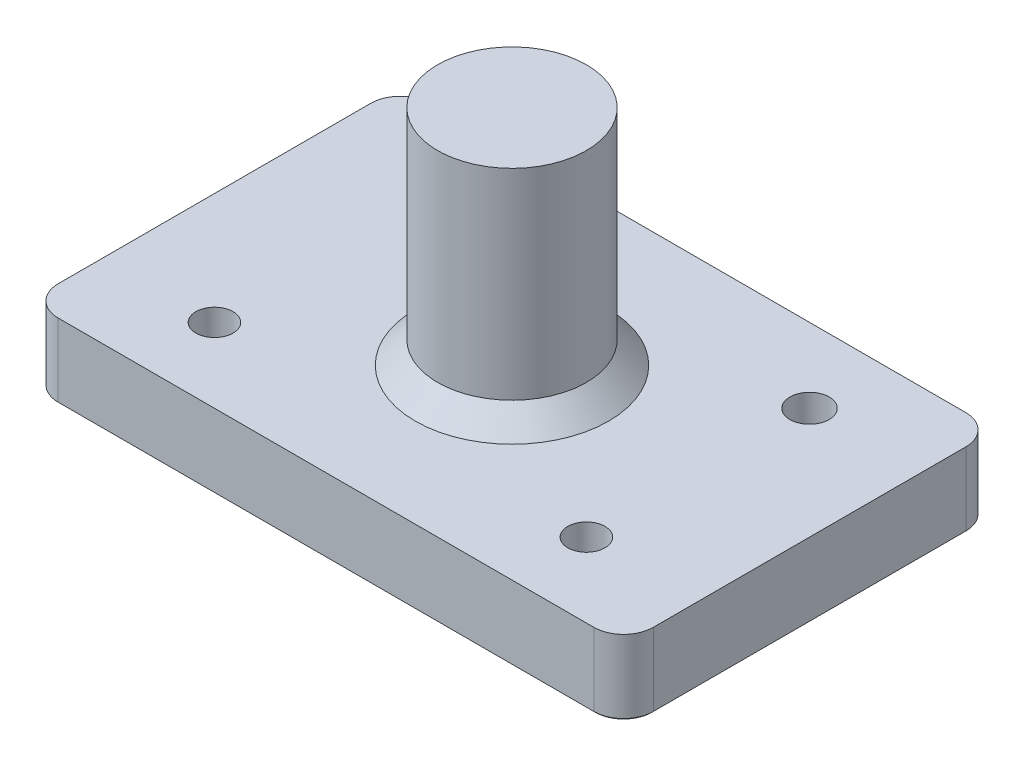
SolidWorks part; units mm, degrees
ref_plane "Front Plane" through (0, 0, 0) normal (0, 0, 1) x (1, 0, 0)
ref_plane "Top Plane" through (0, 0, 0) normal (0, 1, 0) x (1, 0, 0)
ref_plane "Right Plane" through (0, 0, 0) normal (1, 0, 0) x (0, 0, -1)
sketch "Sketch1" plane through (0, 0, 0) normal (0, 1, 0) x (1, 0, 0)
  line L0 (-31.75, 19.05) -> (-31.75, -19.05) construction
  line L1 (-50.8, -31.75) -> (50.8, -31.75)
  line L2 (-50.8, -31.75) -> (-50.8, 31.75)
  line L3 (-50.8, 31.75) -> (50.8, 31.75)
  line L4 (50.8, -31.75) -> (50.8, 31.75)
  line L5 (-50.8, -31.75) -> (50.8, 31.75) construction
  line L6 (-50.8, 31.75) -> (50.8, -31.75) construction
  line L7 (-31.75, -19.05) -> (31.75, -19.05) construction
  line L8 (31.75, -19.05) -> (31.75, 19.05) construction
  line L9 (31.75, 19.05) -> (-31.75, 19.05) construction
  line L10 (-31.75, 19.05) -> (31.75, -19.05) construction
  line L11 (31.75, 19.05) -> (-31.75, -19.05) construction
  circle A0 centre (-31.75, 19.05) radius 3.175
  circle A1 centre (-31.75, -19.05) radius 3.175
  circle A2 centre (31.75, -19.05) radius 3.175
  circle A3 centre (31.75, 19.05) radius 3.3492
  point P0 (0, 0)
  point P11 (0, 0)
  dimension "D3" = 6.35
  dimension "D1" = 63.5
  dimension "D2" = 101.6
  dimension "D4" = 63.5
  dimension "D5" = 38.1
extrude "Boss-Extrude1" add sketch "Sketch1" along normal blind 12.7
sketch "Sketch2" plane through (0, 12.7, 0) normal (0, 1, 0) x (1, 0, 0)
  circle A0 centre (0, 0) radius 12.7
  dimension "D1" = 25.4
extrude "Boss-Extrude2" add sketch "Sketch2" along normal blind 38.1
chamfer "Chamfer1" distance 3.81 angle 45 1 edges at (0, 12.7, 12.7)
fillet "Fillet1" radius 5.08 4 edges at (-50.8, 6.35, 31.75) (50.8, 6.35, 31.75) (50.8, 6.35, -31.75) (-50.8, 6.35, -31.75)
chamfer "Chamfer2" distance 0.254 angle 45 12 edges at (31.75, 0, -15.7008) (-31.75, 0, -15.875) (49.3121, 0, 30.2621) (50.8, 0, 0) (49.3121, 0, -30.2621) (0, 0, -31.75) (-49.3121, 0, -30.2621) (-50.8, 0, 0) (-49.3121, 0, 30.2621) (0, 0, 31.75) (-31.75, 0, 22.225) (31.75, 0, 22.225)
